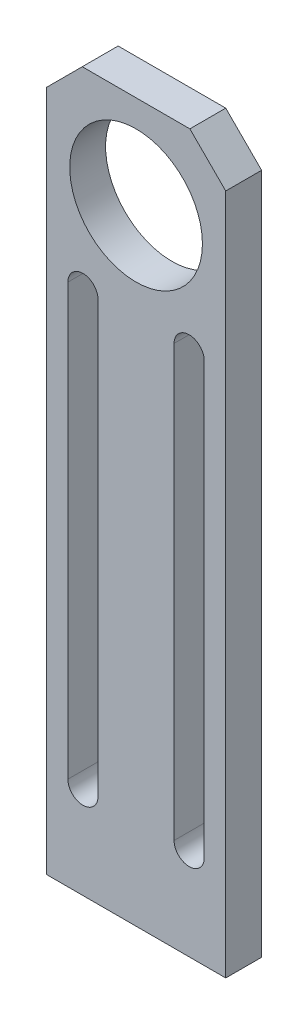
SolidWorks part; units mm, degrees
ref_plane "Front Plane" through (0, 0, 0) normal (0, 0, 1) x (1, 0, 0)
ref_plane "Top Plane" through (0, 0, 0) normal (0, 1, 0) x (1, 0, 0)
ref_plane "Right Plane" through (0, 0, 0) normal (1, 0, 0) x (0, 0, -1)
sketch "Sketch1" plane through (0, 0, 0) normal (0, 0, 1) x (1, 0, 0)
  line L0 (0, 0) -> (0, 50) construction
  line L1 (-7.5, 50) -> (7.5, 50)
  line L2 (-12.5, 45) -> (-12.5, -50)
  line L3 (-12.5, -50) -> (12.5, -50)
  line L4 (12.5, 45) -> (12.5, -50)
  line L5 (-12.5, 50) -> (12.5, -50) construction
  line L6 (-12.5, -50) -> (12.5, 50) construction
  line L7 (7.4, 50) -> (7.4, -50) construction
  line L8 (7.4, 23) -> (7.4, -37) construction
  line L9 (9.5, 23) -> (9.5, -37)
  line L10 (5.3, 23) -> (5.3, -37)
  line L11 (-7.4, 50) -> (-7.4, -50) construction
  line L12 (-7.4, 23) -> (-7.4, -37) construction
  line L13 (-9.5, 23) -> (-9.5, -37)
  line L14 (-5.3, 23) -> (-5.3, -37)
  line L15 (-12.5, 45) -> (-7.5, 50)
  line L16 (7.5, 50) -> (12.5, 45)
  line L17 (-12.5, -45) -> (12.5, -45) construction
  circle A0 centre (0, 37) radius 9.25
  arc A1 (9.5, 23) -> (5.3, 23) centre (7.4, 23) ccw
  arc A2 (5.3, -37) -> (9.5, -37) centre (7.4, -37) ccw
  arc A3 (-9.5, 23) -> (-5.3, 23) centre (-7.4, 23) cw
  arc A4 (-5.3, -37) -> (-9.5, -37) centre (-7.4, -37) cw
  point P0 (0, 0)
  point P14 (7.4, -7)
  point P23 (-7.4, -7)
  point P32 (8.5, -8.0946)
  point P33 (0, 0)
  dimension "D3" = 18.5
  dimension "D1" = 100
  dimension "D2" = 25
  dimension "D4" = 4.2
  dimension "D5" = 3
  dimension "D6" = 60
  dimension "D7" = 13
  dimension "D8" = 8
  dimension "D9" = 5
extrude "Boss-Extrude1" add sketch "Sketch1" along normal mid plane 5
